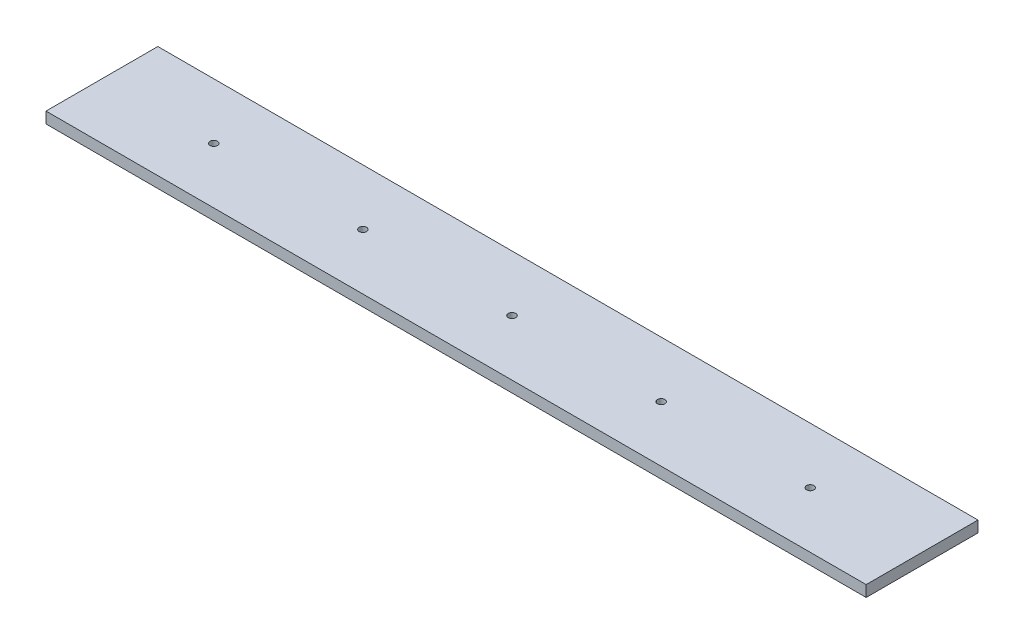
SolidWorks part; units mm, degrees
ref_plane "Front Plane" through (0, 0, 0) normal (0, 0, 1) x (1, 0, 0)
ref_plane "Top Plane" through (0, 0, 0) normal (0, 1, 0) x (1, 0, 0)
ref_plane "Right Plane" through (0, 0, 0) normal (1, 0, 0) x (0, 0, -1)
sketch "Sketch1" plane through (0, 0, 0) normal (0, 1, 0) x (1, 0, 0)
  line L0 (140, 2.5) -> (-80, 2.5) construction
  line L1 (-80, -12.5) -> (140, -12.5)
  line L2 (-80, -12.5) -> (-80, 17.5)
  line L3 (-80, 17.5) -> (140, 17.5)
  line L4 (140, -12.5) -> (140, 17.5)
  line L5 (30, 17.5) -> (30, -12.5) construction
  circle A1 centre (-50, 2.5) radius 1
  circle A2 centre (-10, 2.5) radius 1
  circle A3 centre (30, 2.5) radius 1
  circle A4 centre (70, 2.5) radius 1
  circle A5 centre (110, 2.5) radius 1
  point P0 (0, 0)
  dimension "D3" = 30
  dimension "D4" = 2
  dimension "D6" = 40
  dimension "D1" = 30
  dimension "D2" = 220
  dimension "D5" = 5
extrude "Boss-Extrude1" add sketch "Sketch1" along normal blind 3
ref_plane "Plane1" through (30, 0, 0) normal (-1, 0, 0) x (0, 0, 1)
